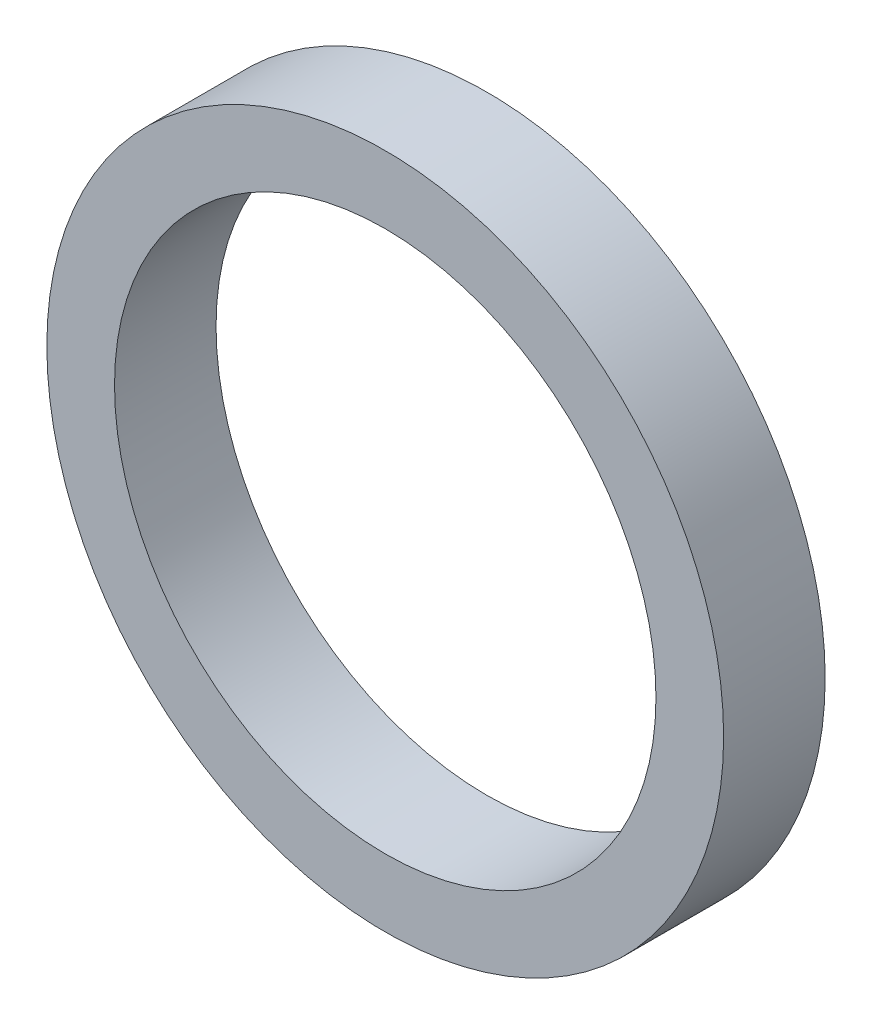
SolidWorks part; units mm, degrees
material "Polyetheretherketone (PEEK)"
ref_plane "Front Plane" through (0, 0, 0) normal (0, 0, 1) x (1, 0, 0)
ref_plane "Top Plane" through (0, 0, 0) normal (0, 1, 0) x (1, 0, 0)
ref_plane "Right Plane" through (0, 0, 0) normal (1, 0, 0) x (0, 0, -1)
sketch "Sketch1" plane through (0, 0, 0) normal (0, 0, 1) x (1, 0, 0)
  circle A0 centre (0, 0) radius 5
  circle A1 centre (0, 0) radius 4
  dimension "D1" = 8
  dimension "D2" = 10
extrude "Boss-Extrude1" add sketch "Sketch1" along normal mid plane 1.5
